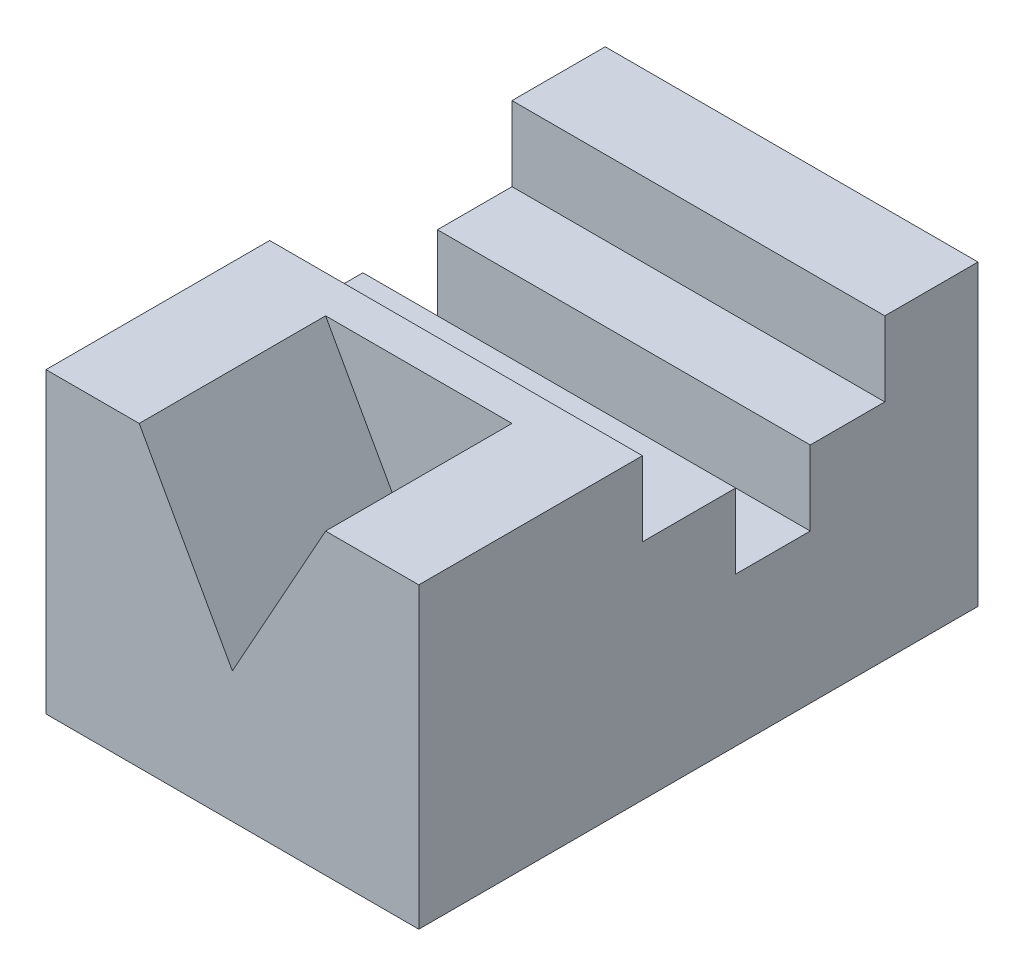
SolidWorks part; units mm, degrees
ref_plane "Front Plane" through (0, 0, 0) normal (0, 0, 1) x (1, 0, 0)
ref_plane "Top Plane" through (0, 0, 0) normal (0, 1, 0) x (1, 0, 0)
ref_plane "Right Plane" through (0, 0, 0) normal (1, 0, 0) x (0, 0, -1)
sketch "Sketch1" plane through (0, 0, 0) normal (0, 1, 0) x (1, 0, 0)
  line L1 (-50, -75) -> (50, -75)
  line L2 (-50, -75) -> (-50, 75)
  line L3 (-50, 75) -> (50, 75)
  line L4 (50, -75) -> (50, 75)
  point P0 (0, 0)
  point P8 (-32.4561, 81.1404)
  dimension "D1" = 150
  dimension "D2" = 100
  dimension "D3" = 50
  dimension "D4" = 75
extrude "Boss-Extrude1" add sketch "Sketch1" along normal blind 80
sketch "Sketch2" plane through (0, 0, 75) normal (0, 0, 1) x (1, 0, 0)
  line L0 (50, 0) -> (-50, 0)
  line L1 (-50, 0) -> (-50, 80)
  line L2 (-50, 80) -> (-25, 80)
  line L3 (-50, 80) -> (50, 80) construction
  line L4 (-25, 80) -> (0, 35)
  line L5 (0, 35) -> (25, 80)
  line L6 (25, 80) -> (50, 80)
  line L7 (50, 80) -> (50, 0)
  dimension "D1" = 25
  dimension "D2" = 25
  dimension "D3" = 50
  dimension "D4" = 45
extrude "Cut-Extrude2" cut sketch "Sketch2" against normal blind 50 flip side to cut contours L4 L5 L6 L7 L0 L1 L2
sketch "Sketch4" plane through (-50, 0, 0) normal (-1, 0, 0) x (0, 0, 1)
  line L0 (-75, 80) -> (-50, 80)
  line L1 (-75, 80) -> (75, 80) construction
  line L2 (-50, 80) -> (-50, 60)
  line L3 (-50, 60) -> (-30, 60)
  line L4 (-30, 60) -> (-30, 40)
  line L5 (-30, 40) -> (-10, 40)
  line L6 (-10, 40) -> (-10, 60)
  line L7 (-10, 60) -> (15, 60)
  line L9 (15, 60) -> (15, 80)
  line L10 (15, 80) -> (75, 80)
  line L11 (-75, 80) -> (-75, 0)
  line L12 (-75, 0) -> (75, 0)
  line L13 (75, 0) -> (75, 80)
  dimension "D1" = 25
  dimension "D2" = 20
  dimension "D3" = 20
  dimension "D4" = 20
  dimension "D5" = 20
  dimension "D6" = 60
  dimension "D7" = 20
extrude "Cut-Extrude3" cut sketch "Sketch4" against normal blind 100 flip side to cut
